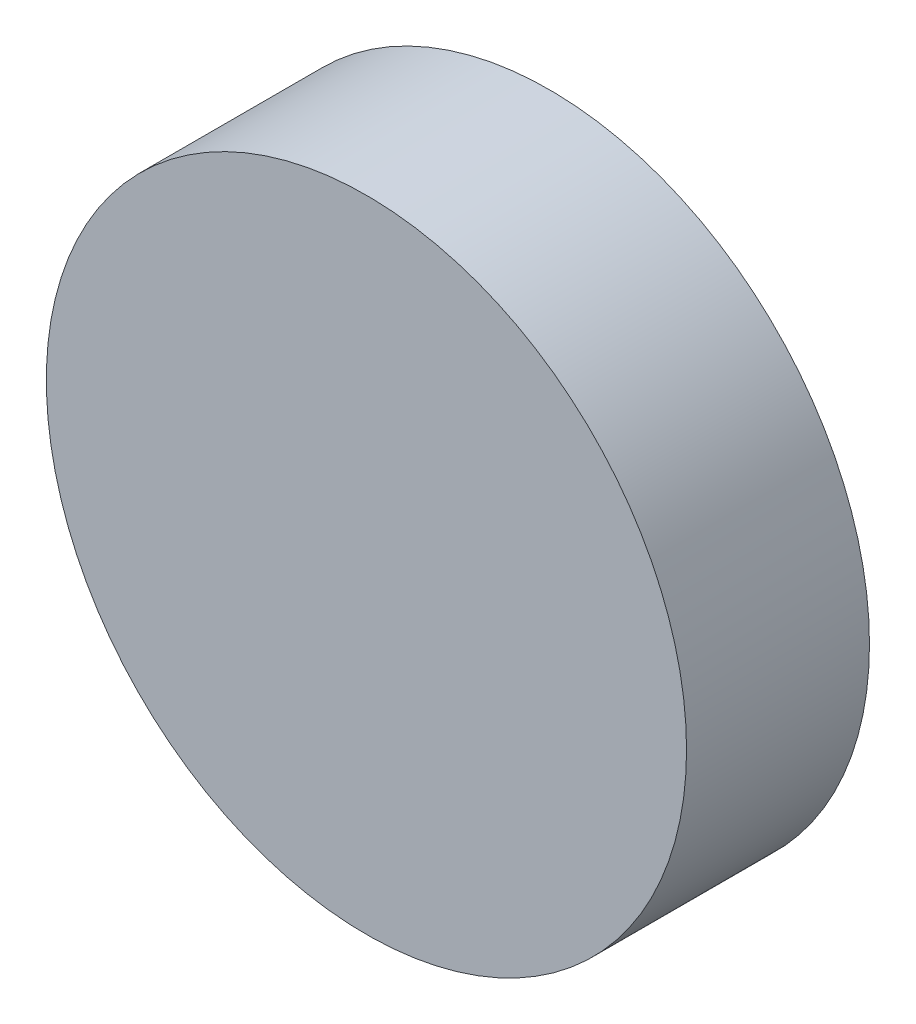
SolidWorks part; units mm, degrees
ref_plane "Plan de face" through (0, 0, 0) normal (0, 0, 1) x (1, 0, 0)
ref_plane "Plan de dessus" through (0, 0, 0) normal (0, 1, 0) x (1, 0, 0)
ref_plane "Plan de droite" through (0, 0, 0) normal (1, 0, 0) x (0, 0, -1)
sketch "Esquisse1" plane through (0, 0, 0) normal (0, 0, 1) x (1, 0, 0)
  circle A0 centre (0, 0) radius 35
  dimension "D1" = 70
extrude "Boss.-Extru.1" add sketch "Esquisse1" along normal blind 20
